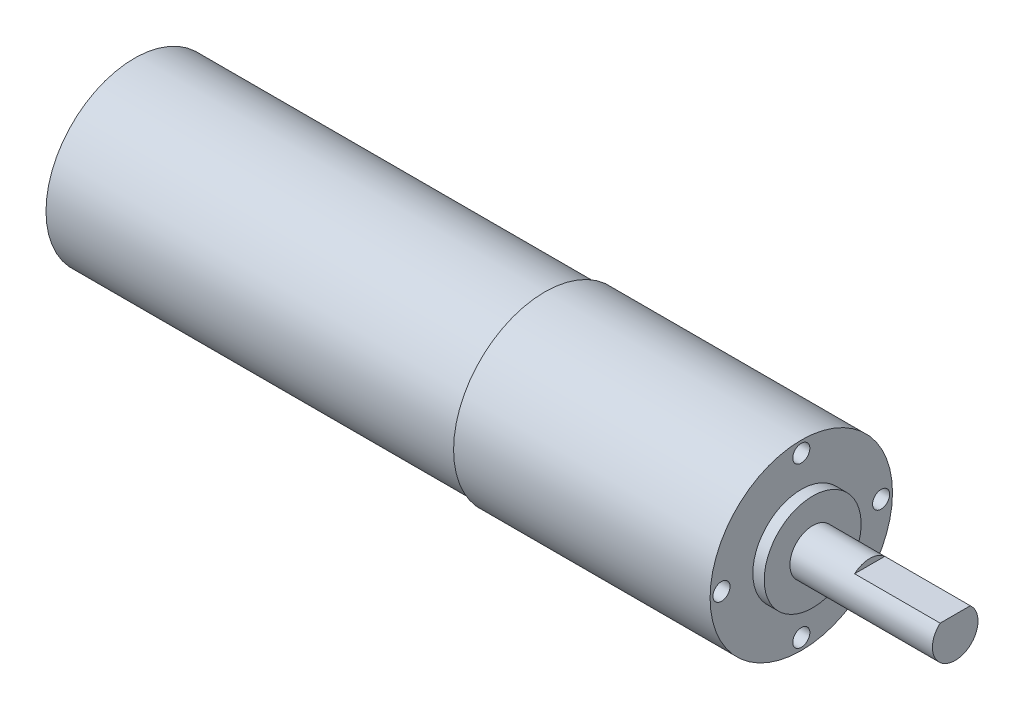
SolidWorks part; units mm, degrees
ref_plane "Front Plane" through (0, 0, 0) normal (0, 0, 1) x (1, 0, 0)
ref_plane "Top Plane" through (0, 0, 0) normal (0, 1, 0) x (1, 0, 0)
ref_plane "Right Plane" through (0, 0, 0) normal (1, 0, 0) x (0, 0, -1)
sketch "Sketch1" plane through (0, 0, 0) normal (0, 0, 1) x (1, 0, 0)
  line L0 (0, 0) -> (0, 15.5)
  line L1 (0, 15.5) -> (72, 15.5)
  line L2 (72, 15.5) -> (72, 16)
  line L3 (72, 16) -> (117, 16)
  line L4 (117, 16) -> (117, 8.5)
  line L5 (117, 8.5) -> (119, 8.5)
  line L6 (119, 8.5) -> (119, 4)
  line L7 (119, 4) -> (144, 4)
  line L8 (144, 4) -> (144, 0)
  line L9 (0, 0) -> (144, 0) construction
  line L10 (0, 0) -> (144, 0)
  dimension "D1" = 31
  dimension "D2" = 32
  dimension "D3" = 72
  dimension "D4" = 45
  dimension "D5" = 17
  dimension "D6" = 8
  dimension "D7" = 2
  dimension "D8" = 25
revolve "Revolve1" add sketch "Sketch1" angle 360 about L9
sketch "Sketch2" plane through (144, 0, 0) normal (1, 0, 0) x (0, 0, -1)
  line L0 (-2.6458, 3) -> (2.6458, 3)
  arc A0 (2.6458, 3) -> (-2.6458, 3) centre (0, 0) ccw
  circle A1 centre (0, 0) radius 4 construction
  dimension "D1" = 3
extrude "Cut-Extrude1" cut sketch "Sketch2" against normal blind 15
sketch "Sketch3" plane through (117, 0, 0) normal (1, 0, 0) x (0, 0, -1)
  circle A0 centre (0, 0) radius 14 construction
  circle A1 centre (0, 14) radius 1.5
  circle A3 centre (14, 0) radius 1.5
  circle A4 centre (0, -14) radius 1.5
  circle A5 centre (-14, 0) radius 1.5
  point P14 (0, 0)
  dimension "D1" = 28
  dimension "D2" = 3
  dimension "D3" = 4
extrude "Cut-Extrude2" cut sketch "Sketch3" against normal blind 5
